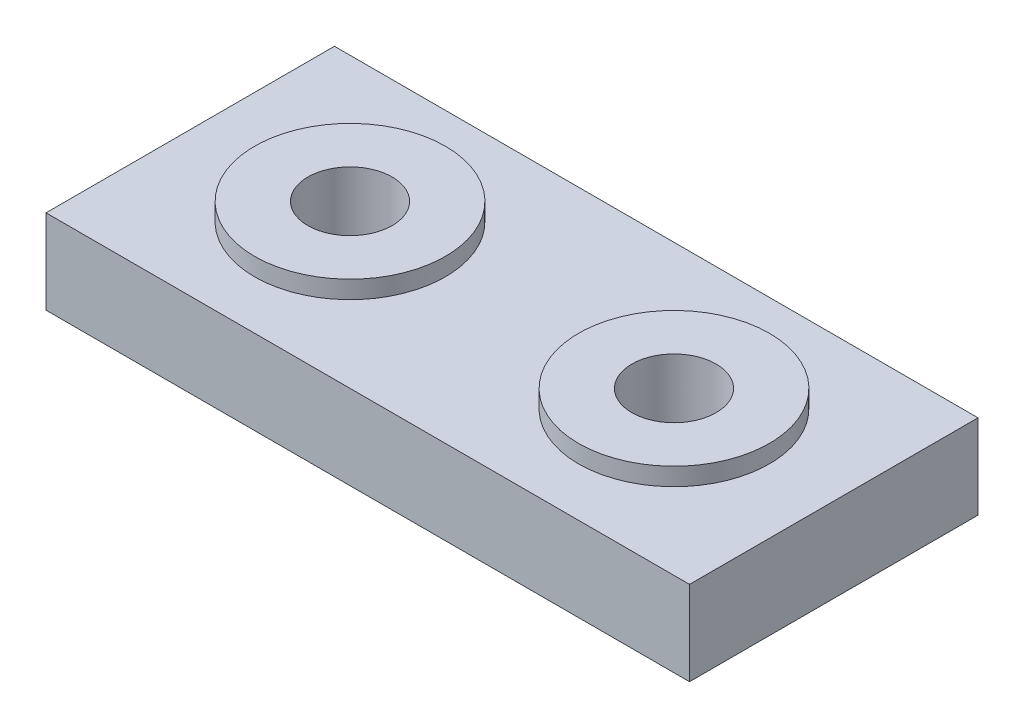
SolidWorks part; units mm, degrees
ref_plane "Front Plane" through (0, 0, 0) normal (0, 0, 1) x (1, 0, 0)
ref_plane "Top Plane" through (0, 0, 0) normal (0, 1, 0) x (1, 0, 0)
ref_plane "Right Plane" through (0, 0, 0) normal (1, 0, 0) x (0, 0, -1)
sketch "Sketch1" plane through (0, 0, 0) normal (0, 1, 0) x (1, 0, 0)
  line L1 (7.25, -3.25) -> (-7.25, -3.25)
  line L2 (7.25, -3.25) -> (7.25, 3.25)
  line L3 (7.25, 3.25) -> (-7.25, 3.25)
  line L4 (-7.25, -3.25) -> (-7.25, 3.25)
  line L5 (7.25, -3.25) -> (-7.25, 3.25) construction
  line L6 (7.25, 3.25) -> (-7.25, -3.25) construction
  point P0 (0, 0)
  dimension "D1" = 6.5
  dimension "D2" = 14.5
extrude "Boss-Extrude1" add sketch "Sketch1" along normal blind 1.9
shell "Shell1" thickness 1.2
sketch "Sketch2" plane through (0, 1.9, 0) normal (0, 1, 0) x (1, 0, 0)
  line L0 (-9.3255, 0) -> (9.5234, 0) construction
  line L1 (-7.25, 3.25) -> (-7.25, -3.25) construction
  line L2 (0, 0) -> (0, -3.8656) construction
  circle A0 centre (-3.65, 0) radius 2.15
  circle A1 centre (-3.65, 0) radius 0.95
  circle A2 centre (3.65, 0) radius 0.95
  circle A3 centre (3.65, 0) radius 2.15
  dimension "D1" = 4.3
  dimension "D3" = 1.2
  dimension "D2" = 3.6
extrude "Boss-Extrude2" add sketch "Sketch2" along normal blind 0.4
sketch "Sketch3" plane through (0, 1.9, 0) normal (0, 1, 0) x (1, 0, 0)
  circle A1 centre (-3.65, 0) radius 0.95
extrude "Cut-Extrude1" cut sketch "Sketch3" against normal blind 3.4
sketch "Sketch4" plane through (0, 1.9, 0) normal (0, 1, 0) x (1, 0, 0)
  circle A1 centre (3.65, 0) radius 0.95
extrude "Cut-Extrude2" cut sketch "Sketch4" against normal blind 3.4
